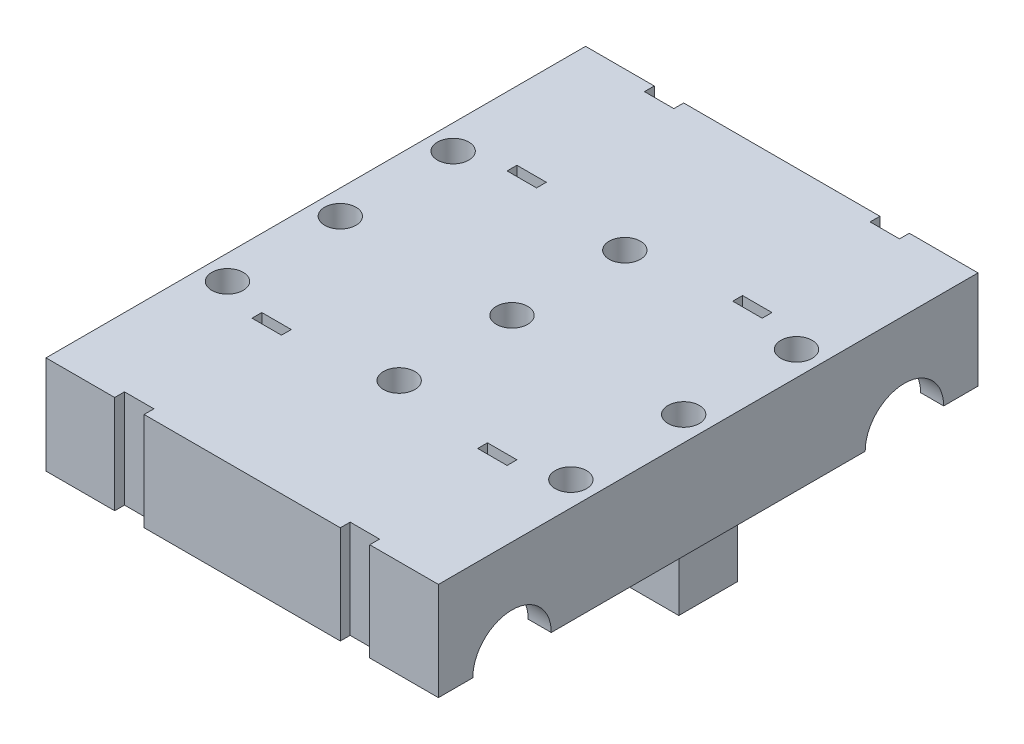
SolidWorks part; units mm, degrees
ref_plane "前基準面" through (0, 0, 0) normal (0, 0, 1) x (1, 0, 0)
ref_plane "上基準面" through (0, 0, 0) normal (0, 1, 0) x (1, 0, 0)
ref_plane "右基準面" through (0, 0, 0) normal (1, 0, 0) x (0, 0, -1)
sketch "草圖1" plane through (0, 0, 0) normal (0, 1, 0) x (1, 0, 0)
  line L1 (-20000, 27500) -> (20000, 27500)
  line L2 (-20000, 27500) -> (-20000, -27500)
  line L3 (-20000, -27500) -> (20000, -27500)
  line L4 (20000, 27500) -> (20000, -27500)
  line L5 (-20000, 27500) -> (20000, -27500) construction
  line L6 (-20000, -27500) -> (20000, 27500) construction
  point P0 (0, 0)
  dimension "D1" = 40000
  dimension "D2" = 55000
extrude "填料-伸長1" add sketch "草圖1" along normal blind 10000
sketch "草圖2" plane through (0, 0, 0) normal (1, 0, 0) x (0, 0, -1)
  line L0 (-27500, 0) -> (27500, 0) construction
  line L1 (0, 6612.3067) -> (0, -10917.8642) construction
  circle A0 centre (-20000, 0) radius 6500
  circle A1 centre (20000, 0) radius 6500
  dimension "D2" = 13000
  dimension "D1" = 40000
extrude "除料-伸長1" cut sketch "草圖2" against normal mid plane 35300
sketch "草圖3" plane through (0, 0, 0) normal (0, -1, 0) x (1, 0, 0)
  line L0 (0, 27500) -> (0, 10480.1678) construction
  line L1 (-20000, 27500) -> (20000, 27500) construction
  line L2 (0, 10480.1678) -> (-17650, 20000) construction
  line L3 (-17650, 13500) -> (-17650, 26500) construction
  line L4 (-17650, 20000) -> (21517.0283, 20000) construction
  line L5 (-15422.8873, 0) -> (31089.3403, 0) construction
  line L6 (-17650, 26500) -> (17650, 26500) construction
  line L7 (-13000, 27500) -> (-10000, 27500)
  line L8 (-13000, 27500) -> (-13000, 26500)
  line L9 (-13000, 26500) -> (-10000, 26500)
  line L10 (-10000, 27500) -> (-10000, 26500)
  line L11 (10000, 27500) -> (10000, 26500)
  line L12 (13000, 26500) -> (10000, 26500)
  line L13 (13000, 27500) -> (13000, 26500)
  line L14 (13000, 27500) -> (10000, 27500)
  line L15 (13000, 12500) -> (10000, 12500)
  line L16 (13000, 12500) -> (13000, 13500)
  line L17 (13000, 13500) -> (10000, 13500)
  line L18 (10000, 12500) -> (10000, 13500)
  line L19 (-10000, 12500) -> (-10000, 13500)
  line L20 (-13000, 13500) -> (-10000, 13500)
  line L21 (-13000, 12500) -> (-13000, 13500)
  line L22 (-13000, 12500) -> (-10000, 12500)
  line L23 (-13000, -12500) -> (-10000, -12500)
  line L24 (-13000, -12500) -> (-13000, -13500)
  line L25 (-13000, -13500) -> (-10000, -13500)
  line L26 (-10000, -12500) -> (-10000, -13500)
  line L27 (10000, -12500) -> (10000, -13500)
  line L28 (13000, -13500) -> (10000, -13500)
  line L29 (13000, -12500) -> (13000, -13500)
  line L30 (13000, -12500) -> (10000, -12500)
  line L31 (13000, -27500) -> (10000, -27500)
  line L32 (13000, -27500) -> (13000, -26500)
  line L33 (13000, -26500) -> (10000, -26500)
  line L34 (10000, -27500) -> (10000, -26500)
  line L35 (-10000, -27500) -> (-10000, -26500)
  line L36 (-13000, -26500) -> (-10000, -26500)
  line L37 (-13000, -27500) -> (-13000, -26500)
  line L38 (-13000, -27500) -> (-10000, -27500)
  dimension "D1" = 3000
  dimension "D2" = 10000
extrude "除料-伸長2" cut sketch "草圖3" against normal blind 35300
sketch "草圖4" plane through (0, 10000, 0) normal (0, 1, 0) x (1, 0, 0)
  line L0 (-20000, 0) -> (20000, 0) construction
  line L1 (20000, -27500) -> (20000, 27500) construction
  line L2 (-6798.2913, 6000) -> (6798.2913, 6000) construction
  line L3 (-12139.721, -6000) -> (11456.8617, -6000) construction
  line L4 (13000, 3000) -> (13000, 1000)
  line L5 (-10000, 9000) -> (10000, 9000) construction
  line L6 (-10000, 9000) -> (-10000, 3000) construction
  line L7 (-10000, 3000) -> (10000, 3000) construction
  line L8 (10000, 9000) -> (10000, 3000) construction
  line L9 (-10000, 9000) -> (10000, 3000) construction
  line L10 (-10000, 3000) -> (10000, 9000) construction
  line L11 (-10000, 9000) -> (-13000, 9000)
  line L12 (-10000, 9000) -> (-10000, 11000)
  line L13 (-10000, 11000) -> (-13000, 11000)
  line L14 (-13000, 9000) -> (-13000, 11000)
  line L15 (10000, 9000) -> (13000, 9000)
  line L16 (10000, 9000) -> (10000, 11000)
  line L17 (10000, 11000) -> (13000, 11000)
  line L18 (13000, 9000) -> (13000, 11000)
  line L19 (10000, 3000) -> (13000, 3000)
  line L20 (10000, 3000) -> (10000, 1000)
  line L21 (10000, 1000) -> (13000, 1000)
  line L22 (-10000, 3000) -> (-10000, 1000)
  line L23 (-10000, 3000) -> (-13000, 3000)
  line L24 (-13000, 3000) -> (-13000, 1000)
  line L25 (-10000, 1000) -> (-13000, 1000)
  line L26 (0, 0) -> (0, 15008.9326) construction
  point P8 (0, 6000)
  point P26 (0, 0)
  dimension "D1" = 6000
  dimension "D2" = 6000
  dimension "D3" = 6000
  dimension "D4" = 20000
  dimension "D5" = 2000
  dimension "D6" = 2000
  dimension "D7" = 3000
  dimension "D8" = 3000
sketch "草圖5" plane through (0, 0, 0) normal (0, -1, 0) x (1, 0, 0)
  line L0 (-24810.5547, 0) -> (39681.7129, 0) construction
  line L1 (39681.7129, 0) -> (0, 29704.3797) construction
  line L2 (0, 29704.3797) -> (0, -29097.3937) construction
  line L4 (-17500, 11500) -> (17500, 11500) construction
  line L5 (-17500, 11500) -> (-17500, -11500) construction
  line L6 (-17500, -11500) -> (17500, -11500) construction
  line L7 (17500, 11500) -> (17500, -11500) construction
  line L8 (-17500, 11500) -> (17500, -11500) construction
  line L9 (-17500, -11500) -> (17500, 11500) construction
  circle A0 centre (-17500, 11500) radius 1600
  circle A1 centre (17500, 11500) radius 1600
  circle A2 centre (17500, -11500) radius 1600
  circle A3 centre (-17500, -11500) radius 1600
  circle A4 centre (0, 11500) radius 1600
  circle A5 centre (0, 0) radius 1600
  circle A6 centre (0, -11500) radius 1600
  circle A7 centre (-17500, 0) radius 1600
  circle A8 centre (17500, 0) radius 1600
  point P5 (0, 0)
  dimension "D3" = 3200
  dimension "D1" = 35000
  dimension "D2" = 23000
extrude "除料-伸長4" cut sketch "草圖5" against normal blind 35300
sketch "草圖7" plane through (20000, 0, 0) normal (1, 0, 0) x (0, 0, -1)
  circle A0 centre (20000, 0) radius 4000
  circle A1 centre (-20000, 0) radius 4000
  dimension "D1" = 8000
  dimension "D2" = 8000
extrude "除料-伸長5" cut sketch "草圖7" against normal blind 100000
scale "縮放比例1" scale about origin uniform scaling yes scale factor 0.001
sketch "草圖9" plane through (0, 0, 0) normal (0, -1, 0) x (1, 0, 0)
  line L0 (0, -2.6) -> (0, -17.1756) construction
  line L1 (-15, -2) -> (-1.6613, -2)
  line L2 (-15, -2) -> (-15, -8)
  line L3 (-15, -8) -> (15, -8)
  line L4 (15, -2) -> (15, -8)
  line L5 (0, 0) -> (0, -15008.9326) construction
  line L6 (1.6613, -2) -> (15, -2)
  circle A0 centre (0, 0) radius 1.6 construction
  arc A1 (-1.6613, -2) -> (1.6613, -2) centre (0, 0) ccw
  dimension "D5" = 5.2
  dimension "D1" = 15
  dimension "D2" = 15
  dimension "D3" = 2
  dimension "D4" = 6
extrude "填料-伸長3" add sketch "草圖9" along normal blind 10
sketch "草圖10" plane through (0, 0, -8) normal (0, 0, -1) x (-1, 0, 0)
  line L0 (15, -10) -> (-15, -10) construction
  line L1 (-9, -3.5) -> (-6, -3.5)
  line L2 (-9, -3.5) -> (-9, -5)
  line L3 (-9, -5) -> (-6, -5)
  line L4 (-6, -3.5) -> (-6, -5)
  line L5 (6, -3.5) -> (9, -3.5)
  line L6 (6, -3.5) -> (6, -5)
  line L7 (6, -5) -> (9, -5)
  line L8 (9, -3.5) -> (9, -5)
  line L9 (15, -10) -> (15, 0) construction
  line L10 (-15, -10) -> (-15, 0) construction
  dimension "D1" = 1.5
  dimension "D2" = 3
  dimension "D3" = 3
  dimension "D4" = 1.5
  dimension "D5" = 5
  dimension "D6" = 5
  dimension "D7" = 6
  dimension "D8" = 6
extrude "除料-伸長6" cut sketch "草圖10" against normal blind 10
